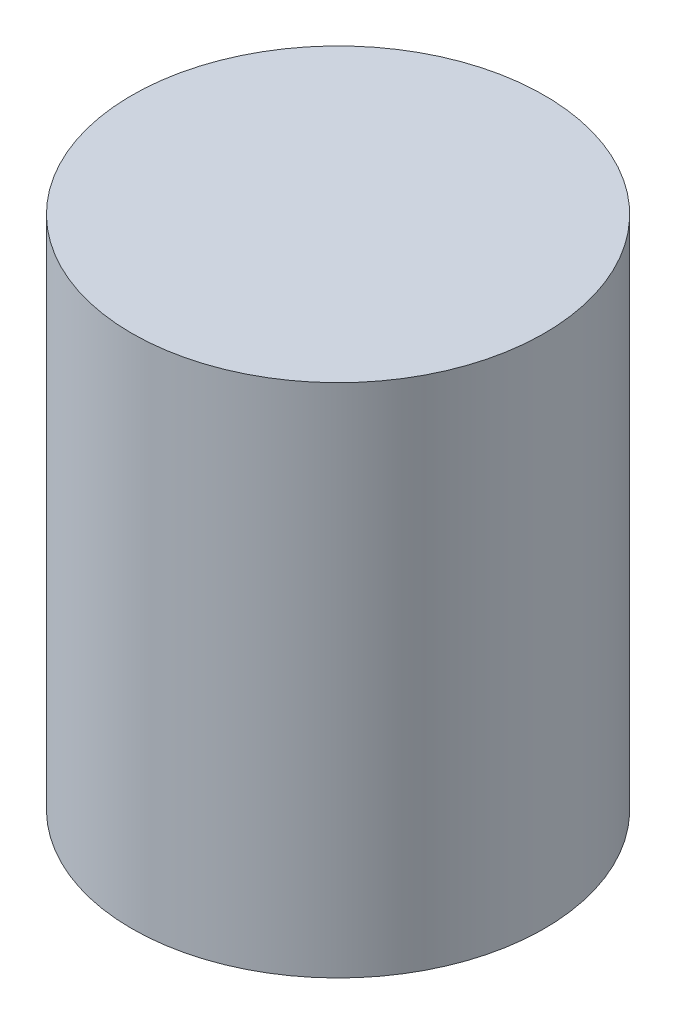
SolidWorks part; units mm, degrees
ref_plane "Front Plane" through (0, 0, 0) normal (0, 0, 1) x (1, 0, 0)
ref_plane "Top Plane" through (0, 0, 0) normal (0, 1, 0) x (1, 0, 0)
ref_plane "Right Plane" through (0, 0, 0) normal (1, 0, 0) x (0, 0, -1)
sketch "Sketch1" plane through (0, 0, 0) normal (0, 1, 0) x (1, 0, 0)
  circle A0 centre (0, 0) radius 200
  dimension "D1" = 400
extrude "Boss-Extrude1" add sketch "Sketch1" along normal blind 500
